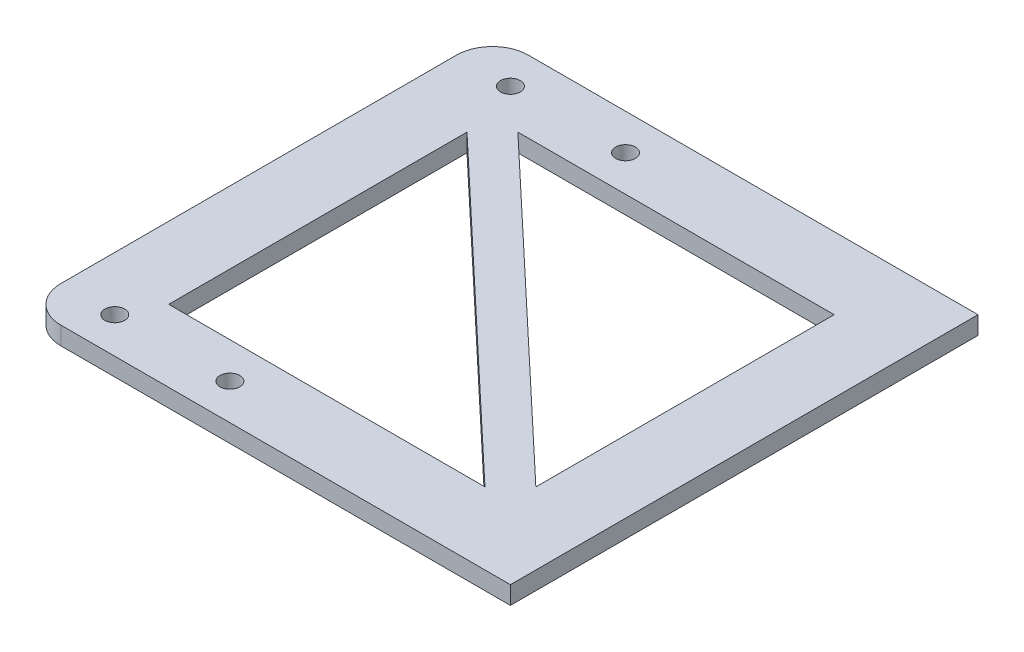
SolidWorks part; units mm, degrees
ref_plane "Front Plane" through (0, 0, 0) normal (0, 0, 1) x (1, 0, 0)
ref_plane "Top Plane" through (0, 0, 0) normal (0, 1, 0) x (1, 0, 0)
ref_plane "Right Plane" through (0, 0, 0) normal (1, 0, 0) x (0, 0, -1)
sketch "Sketch1" plane through (0, 0, 0) normal (0, 1, 0) x (1, 0, 0)
  line L0 (0, 0) -> (0, 130)
  line L1 (0, 130) -> (135, 130)
  line L2 (135, 130) -> (135, 0)
  line L3 (135, 0) -> (0, 0)
  line L4 (0, 65) -> (135, 65) construction
  line L5 (20, 102.9259) -> (107.9259, 20)
  line L10 (27.0741, 110) -> (20, 110) construction
  line L11 (27.0741, 110) -> (115, 27.0741)
  line L12 (27.0741, 110) -> (115, 110)
  line L13 (115, 110) -> (115, 27.0741)
  line L14 (107.9259, 20) -> (20, 20)
  line L15 (20, 20) -> (20, 102.9259)
  line L16 (20, 110) -> (20, 102.9259) construction
  line L17 (115, 27.0741) -> (115, 20) construction
  line L18 (115, 20) -> (107.9259, 20) construction
  circle A0 centre (15, 10) radius 2.75
  circle A1 centre (47, 10) radius 2.75
  circle A2 centre (15, 120) radius 2.75
  circle A3 centre (47, 120) radius 2.75
  dimension "D2" = 5.5
  dimension "D3" = 110
  dimension "D4" = 32
  dimension "D5" = 55
  dimension "D6" = 15
  dimension "D1" = 130
  dimension "D7" = 135
  dimension "D8" = 10
  dimension "D9" = 20
  dimension "D10" = 20
  dimension "D11" = 20
  dimension "D12" = 20
extrude "Boss-Extrude2" add sketch "Sketch1" along normal blind 5
fillet "Fillet1" radius 10 2 edges at (0, 2.5, -130) (0, 2.5, 0)
